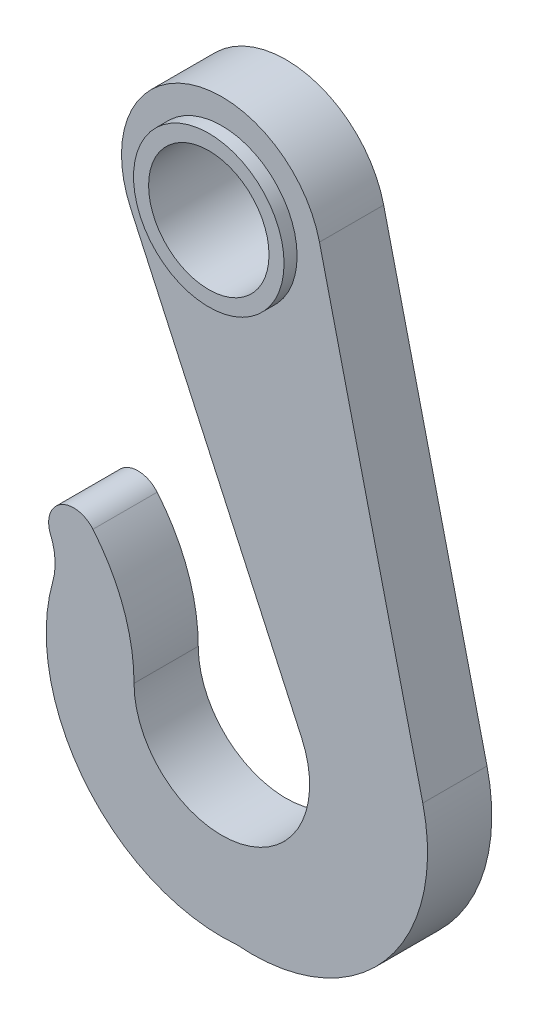
SolidWorks part; units mm, degrees
ref_plane "Alzado" through (0, 0, 0) normal (0, 0, 1) x (1, 0, 0)
ref_plane "Planta" through (0, 0, 0) normal (0, 1, 0) x (1, 0, 0)
ref_plane "Vista lateral" through (0, 0, 0) normal (1, 0, 0) x (0, 0, -1)
sketch "Croquis2" plane through (0, 0, 0) normal (0, 0, 1) x (1, 0, 0)
  line L0 (0, 0) -> (0, -4.5) construction
  line L1 (0, -4.5) -> (0.3, -4.5) construction
  line L2 (0.9728, 0.2315) -> (2.0025, -4.0948)
  line L3 (-0.9091, -0.4167) -> (0.7954, -4.1354)
  line L4 (-6.8904, -4.5) -> (6.8904, -4.5) construction
  line L5 (-2.625, -4.5) -> (3.1807, 0.3716) construction
  arc A0 (0.9728, 0.2315) -> (-0.9091, -0.4167) centre (0, 0) ccw
  arc A1 (0.15, -6.2436) -> (2.0025, -4.0948) centre (0.3, -4.5) ccw
  arc A2 (-0.875, -4.5) -> (0.7954, -4.1354) centre (0, -4.5) ccw
  arc A4 (-0.875, -4.5) -> (-1.2844, -3.3751) centre (-2.625, -4.5) ccw
  arc A5 (-1.2844, -3.3751) -> (-1.7069, -3.6314) centre (-1.4759, -3.5358) ccw
  arc A7 (-1.684, -4.024) -> (-1.7069, -3.6314) centre (-2.2614, -3.8607) ccw
  arc A8 (-1.684, -4.024) -> (0.15, -6.2436) centre (0, -4.5) ccw
  point P14 (0, -4.5)
  dimension "D1" = 2
  dimension "D4" = 3.5
  dimension "D6" = 0.5
  dimension "D7" = 0.875
  dimension "D8" = 1.2
  dimension "D9" = 1.75
  dimension "D2" = 4.5
  dimension "D3" = 0.3
  dimension "D5" = 40
extrude "Saliente-Extruir1" add sketch "Croquis2" along normal blind 0.64 contours L2 A1 A8 A7 A5 A4 A2 L3 A0
sketch "Croquis4" plane through (0, 0, 0.64) normal (0, 0, 1) x (1, 0, 0)
  circle A0 centre (0, 0) radius 0.75
  circle A1 centre (0, 0) radius 0.6
  dimension "D1" = 1.5
  dimension "D2" = 1.2
extrude "Saliente-Extruir2" add sketch "Croquis4" along normal blind 0.13
sketch "Croquis5" plane through (0, 0, 0) normal (0, 0, -1) x (-1, 0, 0)
  circle A0 centre (0, 0) radius 0.6 construction
  circle A1 centre (0, 0) radius 0.6
  circle A2 centre (0, 0) radius 0.75 construction
  circle A3 centre (0, 0) radius 0.75
extrude "Saliente-Extruir3" add sketch "Croquis5" along normal blind 0.13
sketch "Croquis6" plane through (0, 0, 0.64) normal (0, 0, 1) x (1, 0, 0)
  circle A0 centre (0, 0) radius 0.6 construction
  circle A1 centre (0, 0) radius 0.6
extrude "Cortar-Extruir1" cut sketch "Croquis6" against normal blind 0.64 contours A1
